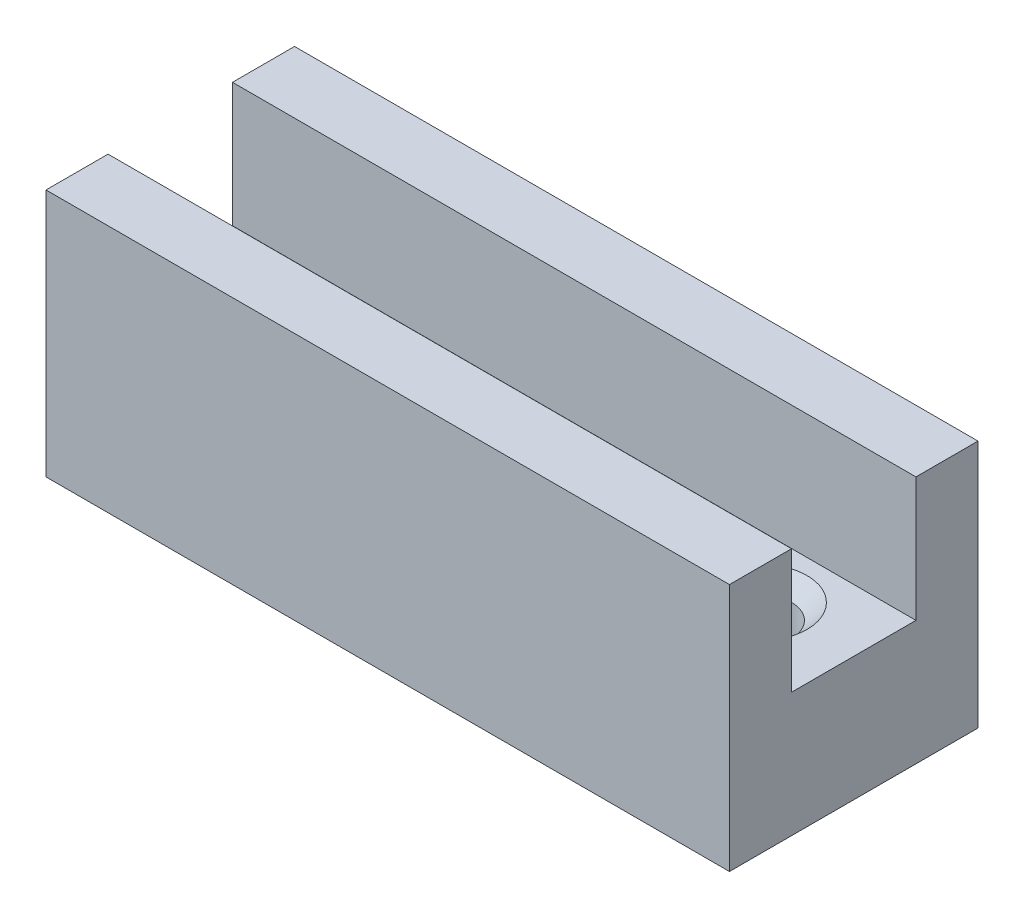
SolidWorks part; units mm, degrees
ref_plane "Front Plane" through (0, 0, 0) normal (0, 0, 1) x (1, 0, 0)
ref_plane "Top Plane" through (0, 0, 0) normal (0, 1, 0) x (1, 0, 0)
ref_plane "Right Plane" through (0, 0, 0) normal (1, 0, 0) x (0, 0, -1)
sketch "Sketch1" plane through (0, 0, 0) normal (0, 0, 1) x (1, 0, 0)
  line L1 (0, 0) -> (279.4, 0)
  line L2 (0, 0) -> (0, 101.6)
  line L3 (0, 101.6) -> (279.4, 101.6)
  line L4 (279.4, 0) -> (279.4, 101.6)
  dimension "D1" = 279.4
  dimension "D2" = 101.6
extrude "Boss-Extrude1" add sketch "Sketch1" along normal blind 101.6
sketch "Sketch2" plane through (0, 101.6, 0) normal (0, 1, 0) x (1, 0, 0)
  line L0 (0, -101.6) -> (0, -76.234)
  line L1 (0, -101.6) -> (0, 0) construction
  line L2 (0, -76.234) -> (0, -25.366)
  line L3 (0, -25.366) -> (279.4, -25.366)
  line L4 (279.4, -101.6) -> (279.4, 0) construction
  line L5 (279.4, -25.366) -> (279.4, -76.234)
  line L6 (279.4, -76.234) -> (0, -76.234)
  line M2 (0, 0) -> (0, -101.6)
  line M4 (279.4, -101.6) -> (279.4, 0)
extrude "Cut-Extrude1" cut sketch "Sketch2" against normal blind 50.8 contours L6 L3 M4 M2
sketch "Sketch3" plane through (0, 50.8, 0) normal (0, 1, 0) x (1, 0, 0)
  line L0 (279.4, 0) -> (0, 0) construction
  circle A0 centre (38.1, -50.8) radius 12.7
  circle A1 centre (88.9, -50.8) radius 12.7
  circle A2 centre (139.7, -50.8) radius 19.05
  circle A3 centre (190.5, -50.8) radius 12.7
  circle A4 centre (241.3, -50.8) radius 12.7
  circle A5 centre (139.7, -50.8) radius 12.7
  dimension "D1" = 38.1
  dimension "D2" = 50.8
  dimension "D3" = 50.8
  dimension "D4" = 50.8
  dimension "D5" = 50.8
  dimension "D6" = 25.4
  dimension "D7" = 25.4
  dimension "D8" = 38.1
  dimension "D9" = 25.4
  dimension "D10" = 25.4
  dimension "D11" = 25.4
  dimension "D12" = 50.8
  dimension "D13" = 50.8
extrude "Cut-Extrude5" cut sketch "Sketch3" against normal blind 50.8 contours A0 | A1 | A3 | A4
sketch "Sketch7" plane through (0, 50.8, 0) normal (0, 1, 0) x (1, 0, 0)
  line L0 (279.4, 0) -> (0, 0) construction
  circle A0 centre (139.7, -50.8) radius 19.05
  circle A1 centre (88.9, -50.8) radius 12.7 construction
  dimension "D1" = 50.8
  dimension "D2" = 50.8
extrude "Cut-Extrude6" cut sketch "Sketch7" against normal blind 19.05
sketch "Sketch8" plane through (0, 31.75, 0) normal (0, 1, 0) x (1, 0, 0)
  line L0 (279.4, 0) -> (0, 0) construction
  circle A0 centre (139.7, -50.8) radius 12.7
  circle A1 centre (88.9, -50.8) radius 12.7 construction
  dimension "D1" = 50.8
  dimension "D2" = 50.8
extrude "Cut-Extrude7" cut sketch "Sketch8" against normal blind 76.2 contours A0
fillet "Fillet3" radius 6.35 2 edges at (88.9, 50.8, 63.5) (38.1, 50.8, 63.5)
chamfer "Chamfer3" distance 6.35 angle 45 2 edges at (241.3, 50.8, 63.5) (190.5, 50.8, 63.5)
